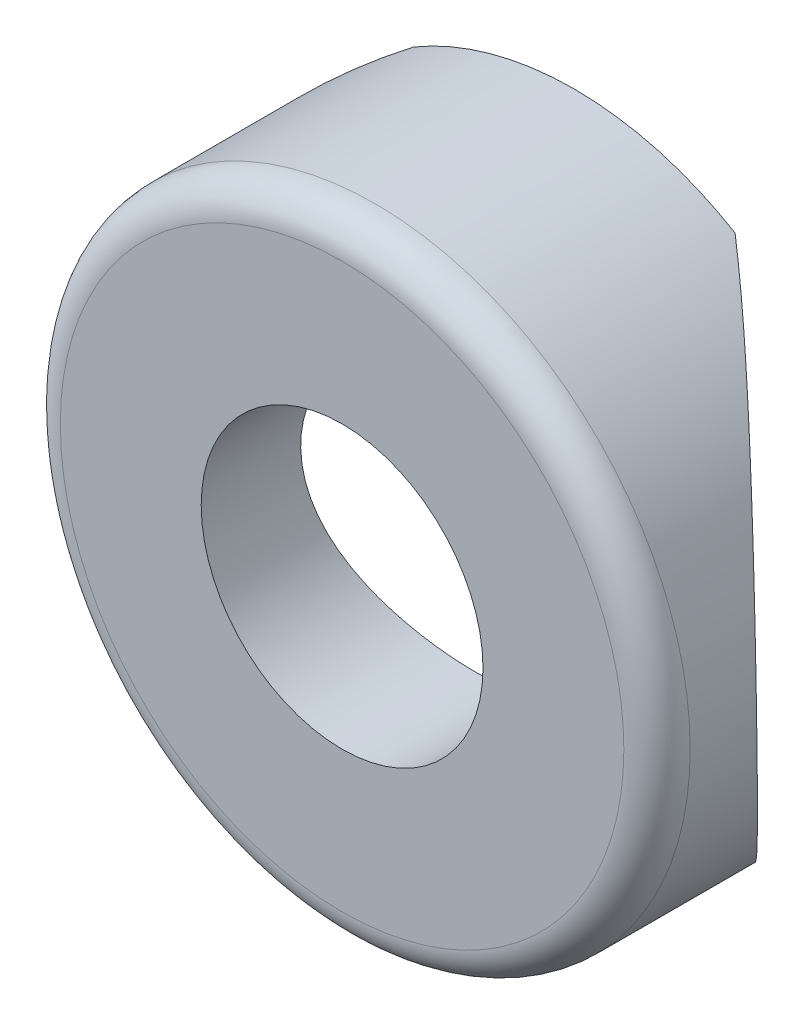
SolidWorks part; units mm, degrees
material "Калифорния"
ref_plane "Спереди" through (0, 0, 0) normal (0, 0, 1) x (1, 0, 0)
ref_plane "Сверху" through (0, 0, 0) normal (0, 1, 0) x (1, 0, 0)
ref_plane "Справа" through (0, 0, 0) normal (1, 0, 0) x (0, 0, -1)
sketch "Эскиз1" plane through (0, 0, 0) normal (0, 0, 1) x (1, 0, 0)
  circle A0 centre (0, 0) radius 9.5
  circle A1 centre (0, 0) radius 4.25
  dimension "D1" = 19
  dimension "D2" = 8.5
extrude "Бобышка-Вытянуть1" add sketch "Эскиз1" along normal blind 7
sketch "Эскиз3" plane through (0, 0, 0) normal (1, 0, 0) x (0, 0, -1)
  line L0 (-7, 9.5) -> (-7, -9.5) construction
  circle A0 centre (6, 0.1661) radius 10
  dimension "D1" = 20
  dimension "D2" = 13
extrude "Вырез-Вытянуть1" cut sketch "Эскиз3" against normal through all and the other way through all
fillet "Скругление1" radius 1 1 edges at (9.5, 0, 7)
